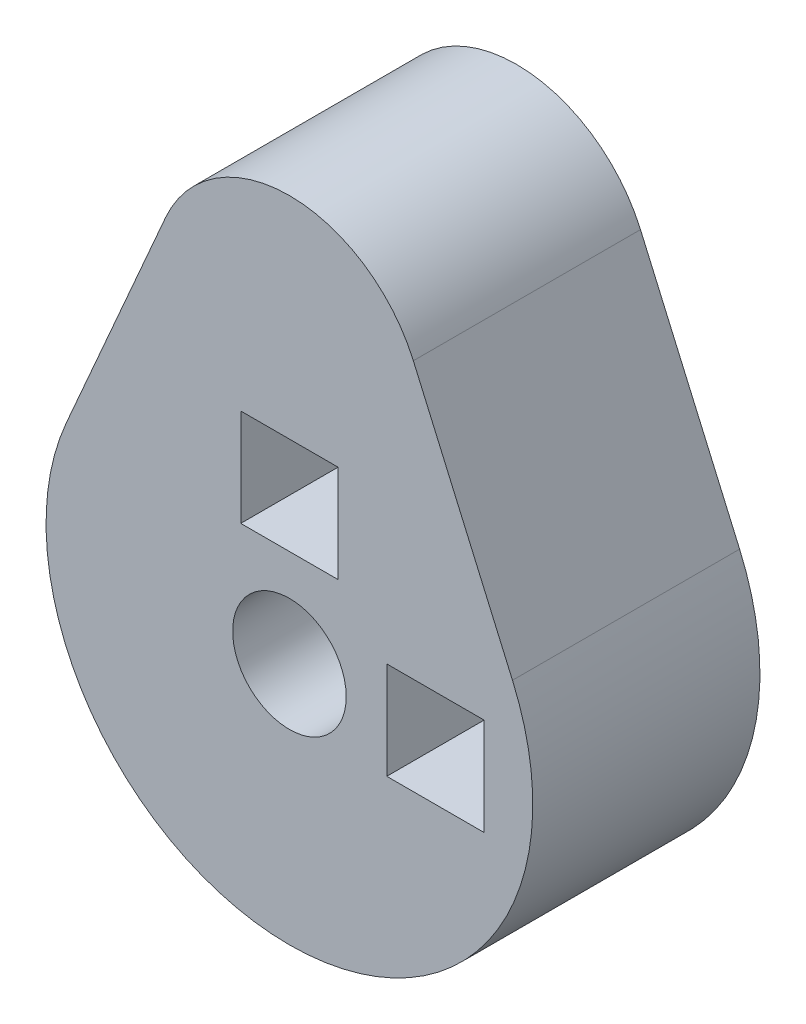
SolidWorks part; units mm, degrees
ref_plane "Front Plane" through (0, 0, 0) normal (0, 0, 1) x (1, 0, 0)
ref_plane "Top Plane" through (0, 0, 0) normal (0, 1, 0) x (1, 0, 0)
ref_plane "Right Plane" through (0, 0, 0) normal (1, 0, 0) x (0, 0, -1)
sketch "Sketch1" plane through (0, 0, 0) normal (0, 0, 1) x (1, 0, 0)
  line L0 (-6.8739, 3) -> (-3.8188, 10)
  line L1 (6.8739, 3) -> (3.8188, 10)
  arc A0 (-6.8739, 3) -> (6.8739, 3) centre (0, 0) ccw
  arc A1 (-3.8188, 10) -> (3.8188, 10) centre (0, 8.3333) cw
  circle A3 centre (0, 0) radius 1.75
  point P1 (0, 12.5)
  point P9 (0, -7.5)
  dimension "D1" = 15
  dimension "D5" = 3.5
  dimension "D2" = 3
  dimension "D3" = 3
  dimension "D4" = 20
extrude "Boss-Extrude1" add sketch "Sketch1" along normal blind 7
sketch "Sketch2" plane through (0, 0, 7) normal (0, 0, 1) x (1, 0, 0)
  line L0 (0, 0) -> (4.5, 0) construction
  line L1 (-1.5, 3) -> (1.5, 3)
  line L2 (-1.5, 3) -> (-1.5, 6)
  line L3 (-1.5, 6) -> (1.5, 6)
  line L4 (1.5, 3) -> (1.5, 6)
  line L5 (-1.5, 3) -> (1.5, 6) construction
  line L6 (-1.5, 6) -> (1.5, 3) construction
  line L8 (3, -1.5) -> (6, -1.5)
  line L9 (3, -1.5) -> (3, 1.5)
  line L10 (3, 1.5) -> (6, 1.5)
  line L11 (6, -1.5) -> (6, 1.5)
  line L12 (3, -1.5) -> (6, 1.5) construction
  line L13 (3, 1.5) -> (6, -1.5) construction
  circle A0 centre (0, 0) radius 4.5 construction
  point P3 (0, 4.5)
  dimension "D1" = 9
  dimension "D2" = 3
extrude "Cut-Extrude1" cut sketch "Sketch2" against normal through all
